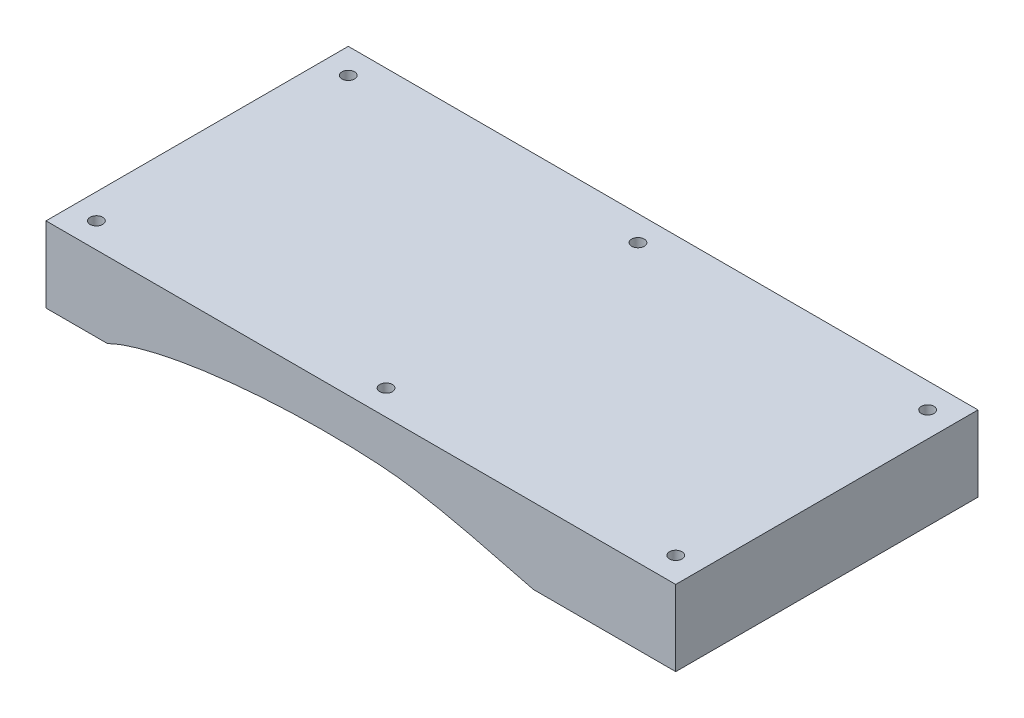
SolidWorks part; units mm, degrees
material "PTFE (general)"
ref_plane "Front Plane" through (0, 0, 0) normal (0, 0, 1) x (1, 0, 0)
ref_plane "Top Plane" through (0, 0, 0) normal (0, 1, 0) x (1, 0, 0)
ref_plane "Right Plane" through (0, 0, 0) normal (1, 0, 0) x (0, 0, -1)
curve "Curve1"
  spline degree 3 poles (0.9879, -0.001, 0) (1.003, 0, 0) (0.9879, 0.001, 0) (0.9756, 0.0029, 0) (0.9509, 0.006, 0) (0.9257, 0.0111, 0) (0.8922, 0.0189, 0) (0.85, 0.0292, 0) (0.8, 0.0421, 0) (0.7501, 0.0546, 0) (0.7002, 0.0662, 0) (0.6502, 0.0761, 0) (0.6002, 0.0839, 0) (0.5501, 0.0876, 0) (0.5, 0.0897, 0) (0.45, 0.0902, 0) (0.4, 0.0894, 0) (0.35, 0.0872, 0) (0.2999, 0.0837, 0) (0.2499, 0.0787, 0) (0.1999, 0.0722, 0) (0.1498, 0.0637, 0) (0.1081, 0.0545, 0) (0.0748, 0.0453, 0) (0.0496, 0.0371, 0) (0.0287, 0.0286, 0) (0.0146, 0.0212, 0) (0.0081, 0.0164, 0) (0.0041, 0.0124, 0) (0.0008, 0.0072, 0) (-0.0004, 0, 0) (0.0008, -0.0072, 0) (0.0041, -0.0124, 0) (0.0081, -0.0164, 0) (0.0146, -0.0212, 0) (0.0287, -0.0286, 0) (0.0496, -0.0371, 0) (0.0748, -0.0453, 0) (0.1081, -0.0545, 0) (0.1498, -0.0637, 0) (0.1999, -0.0722, 0) (0.2499, -0.0787, 0) (0.2999, -0.0837, 0) (0.35, -0.0872, 0) (0.4, -0.0894, 0) (0.45, -0.0902, 0) (0.5, -0.0897, 0) (0.5501, -0.0876, 0) (0.6002, -0.0839, 0) (0.6502, -0.0761, 0) (0.7002, -0.0662, 0) (0.7501, -0.0546, 0) (0.8, -0.0421, 0) (0.842, -0.0313, 0) (0.8753, -0.0231, 0) (0.9087, -0.015, 0) (0.9412, -0.0072, 0) (0.9756, -0.0029, 0) (0.9879, -0.001, 0) (1.003, 0, 0) (0.9879, 0.001, 0) knots -0.02448 -0.010984 -0.00276 0 0.00276 0.010984 0.02448 0.035911 0.049305 0.074294 0.099343 0.12436 0.149265 0.17401 0.198547 0.222904 0.247201 0.271478 0.295756 0.320055 0.344391 0.368787 0.393273 0.417901 0.442781 0.455382 0.46816 0.481314 0.488256 0.491308 0.493017 0.496509 0.500002 0.503494 0.506986 0.508696 0.511748 0.518689 0.531843 0.544621 0.557222 0.582102 0.60673 0.631216 0.655612 0.679949 0.704247 0.728526 0.752803 0.777099 0.801456 0.825994 0.850739 0.875644 0.90066 0.925709 0.938747 0.950698 0.97552 0.989016 0.99724 1 1.00276 1.010984 1.02448 periodic
sketch "Sketch1" plane through (0, 0, 0) normal (0, 0, 1) x (1, 0, 0)
  line L0 (0, 0) -> (-40, 0)
  line L1 (175, 0.3825) -> (175, -0.391) construction
  line L2 (-40, 0) -> (-40, 50)
  line L3 (-40, 50) -> (250, 50)
  line L4 (250, 50) -> (250, 0)
  line L5 (-40, 0) -> (-40, 5)
  line L6 (250, 0) -> (250, 5)
  line L7 (-40, 5) -> (4.407, 5)
  line L8 (250, 5) -> (173.4906, 5)
  line L10 (-20, 5) -> (-20, 35)
  line L11 (-20, 35) -> (230, 35)
  line L12 (230, 35) -> (230, 5)
  line L13 (0, 0) -> (160, 0) construction
  arc A0 (175, 0.3825) -> (175, -0.391) centre (174.9067, -0.0042) cw
  spline S0 degree 3 poles (197.5872, -0.2056) (200.6063, 0) (197.5868, 0.2056) (195.1252, 0.5776) (190.1802, 1.1937) (185.1344, 2.2203) (178.4338, 3.785) (169.9915, 5.8479) (160.0056, 8.4214) (150.023, 10.9293) (140.0327, 13.2422) (130.0396, 15.2245) (120.0397, 16.7768) (110.0103, 17.5195) (100.0043, 17.9361) (89.9996, 18.0394) (79.996, 17.8821) (69.9921, 17.4474) (59.988, 16.7376) (49.9816, 15.7477) (39.9717, 14.4342) (29.9504, 12.7437) (21.617, 10.9015) (14.9666, 9.0538) (9.9288, 7.4256) (5.7467, 5.7158) (2.9192, 4.2411) (1.6254, 3.2787) (0.81, 2.4889) (0.1663, 1.4484) (-0.0831, 0) (0.1663, -1.4484) (0.81, -2.4889) (1.6254, -3.2787) (2.9192, -4.2411) (5.7467, -5.7158) (9.9288, -7.4256) (14.9666, -9.0538) (21.617, -10.9015) (29.9504, -12.7437) (39.9717, -14.4342) (49.9816, -15.7477) (59.988, -16.7376) (69.9921, -17.4474) (79.996, -17.8821) (89.9996, -18.0394) (100.0043, -17.9361) (110.0103, -17.5195) (120.0397, -16.7768) (130.0396, -15.2245) (140.0327, -13.2422) (150.0229, -10.9292) (160.0058, -8.4217) (168.4006, -6.2567) (175.0619, -4.611) (181.7476, -3.0075) (188.2352, -1.4431) (195.1191, -0.5775) (197.5872, -0.2056) (200.6063, 0) (197.5868, 0.2056) knots -0.02448 -0.010984 -0.00276 0 0.00276 0.010984 0.02448 0.035911 0.049305 0.074294 0.099343 0.12436 0.149265 0.17401 0.198547 0.222904 0.247201 0.271478 0.295756 0.320055 0.344391 0.368787 0.393273 0.417901 0.442781 0.455382 0.46816 0.481314 0.488256 0.491308 0.493017 0.496509 0.500002 0.503494 0.506986 0.508696 0.511748 0.518689 0.531843 0.544621 0.557222 0.582102 0.60673 0.631216 0.655612 0.679949 0.704247 0.728526 0.752803 0.777099 0.801456 0.825994 0.850739 0.875644 0.90066 0.925709 0.938747 0.950698 0.97552 0.989016 0.99724 1 1.00276 1.010984 1.02448 only from (200, 0) to (200, 0)
  spline S1 degree 3 poles (175, -0.391) (172.0852, -1.0939) (166.2646, -2.4977) (154.6086, -5.1021) (140.0385, -8.0995) (122.5354, -11.2892) (105.0361, -14.0584) (87.5366, -16.3245) (70.0311, -17.928) (55.4199, -18.5013) (43.7404, -18.2704) (34.9711, -17.6651) (26.1801, -16.4934) (18.8666, -14.858) (13.0417, -12.9137) (8.568, -10.9367) (4.8344, -8.5647) (1.3476, -5.1963) (-0.8977, -0.0042) (1.3476, 5.1878) (4.8344, 8.5562) (8.568, 10.9282) (13.0417, 12.9052) (18.8666, 14.8495) (26.1801, 16.4849) (34.9711, 17.6567) (43.7404, 18.2619) (55.4199, 18.4929) (70.0311, 17.9195) (87.5366, 16.316) (105.0361, 14.0499) (122.5354, 11.2807) (140.0385, 8.0911) (154.6086, 5.0937) (166.2646, 2.4892) (172.0852, 1.0855) (175, 0.3825) knots 0 0 0 0 0.024528 0.048982 0.097703 0.146209 0.194518 0.242628 0.290539 0.338289 0.362155 0.386077 0.410161 0.434654 0.447248 0.460338 0.47462 0.483093 0.5 0.516907 0.52538 0.539662 0.552752 0.565346 0.589839 0.613923 0.637845 0.661711 0.709461 0.757372 0.805482 0.853791 0.902297 0.951018 0.975472 1 1 1 1 construction
  point P15 (174.9067, 0)
  point P17 (186.0106, 9.1612)
  point P21 (4.407, 5)
  point P22 (195.2937, 6.8)
  point P23 (0, 0)
  point P24 (172.3706, 5.2767)
  point P25 (0, 0)
  dimension "D6" = 15
  dimension "D1" = 50
  dimension "D2" = 40
  dimension "D3" = 175
  dimension "D4" = 5
  dimension "D5" = 5
  dimension "D7" = 20
  dimension "D8" = 20
  dimension "D9" = 90
  dimension "D10" = 50
  dimension "D11" = 250
extrude "Boss-Extrude1" add sketch "Sketch1" along normal blind 120 contours L7 S1 L8 L12 L11 L10
sketch "Sketch2" plane through (0, 35, 0) normal (0, 1, 0) x (1, 0, 0)
  line L0 (-20, -60) -> (60, -60)
  line L1 (-20, -120) -> (-20, 0) construction
  circle A0 centre (60, -60) radius 10
ref_plane "Plane1" through (0, 25, 0) normal (0, 1, 0) x (1, 0, 0)
sketch "Sketch5" plane through (0, 25, 0) normal (0, 1, 0) x (1, 0, 0)
  line L0 (-20, -120) -> (-20, 0) construction
  line L1 (-10, 0) -> (-20, 0) construction
  line L2 (-10, 0) -> (-10, -10) construction
  line L3 (-10, -10) -> (-20, -10) construction
  line L4 (-20, 0) -> (-20, -10) construction
  line L5 (-10, -10) -> (220, -10) construction
  line L6 (230, 0) -> (220, 0) construction
  line L7 (230, 0) -> (230, -10) construction
  line L8 (230, -10) -> (220, -10) construction
  line L9 (220, 0) -> (220, -10) construction
  line L10 (230, -120) -> (220, -120) construction
  line L11 (230, -120) -> (230, -110) construction
  line L12 (230, -110) -> (220, -110) construction
  line L13 (220, -120) -> (220, -110) construction
  line L14 (-20, -120) -> (-10, -120) construction
  line L15 (-20, -120) -> (-20, -110) construction
  line L16 (-20, -110) -> (-10, -110) construction
  line L17 (-10, -120) -> (-10, -110) construction
  line L18 (-10, -10) -> (-10, -110) construction
  line L19 (-10, -110) -> (220, -110) construction
  line L20 (220, -110) -> (220, -10) construction
  point P4 (220, -5)
  dimension "D1" = 10
  dimension "D2" = 10
  dimension "D3" = 10
hole_wizard "Ø5.0mm Dowel Hole1" positions "Sketch9" profile "Sketch10" hole size "Ø5.0" standard "ISO"
sketch "Sketch9" plane through (0, 25, 0) normal (0, 1, 0) x (1, 0, 0)
  line L0 (-10, -110) -> (220, -110) construction
  line L1 (-10, -10) -> (220, -10) construction
  point P0 (-10, -10)
  point P3 (220, -10)
  point P6 (220, -110)
  point P9 (105, -110)
  point P13 (-10, -110)
  point P16 (105, -10)
sketch "Sketch10" plane through (-10, 25, 10) normal (1, 0, 0) x (0, 0, -1)
  line L0 (0, 0) -> (0, 10)
  line L1 (0, 10) -> (2.5, 10)
  line L2 (2.5, 10) -> (2.5, 0)
  line L5 (2.5, 0) -> (0, 0)
  line L11 (0, -6.35) -> (0, 107.95) construction
  dimension "Thru Hole Dia." = 5
  dimension "Thru Hole Depth" = 10
hole_wizard "Ø10.0mm Dowel Hole1" positions "Sketch12" profile "Sketch13" hole size "Ø10.0" standard "ISO"
sketch "Sketch12" plane through (0, 25, 0) normal (0, 1, 0) x (1, 0, 0)
  line L0 (-10, -10) -> (220, -10) construction
  line L1 (-10, -110) -> (220, -110) construction
  point P0 (-10, -10)
  point P3 (105, -10)
  point P7 (220, -10)
  point P10 (220, -110)
  point P13 (105, -110)
  point P17 (-10, -110)
sketch "Sketch13" plane through (-10, 25, 10) normal (1, 0, 0) x (0, 0, 1)
  line L0 (0, 0) -> (0, 20)
  line L1 (0, 20) -> (5, 20)
  line L2 (5, 20) -> (5, 0)
  line L5 (5, 0) -> (0, 0)
  line L11 (0, -6.35) -> (0, 107.95) construction
  dimension "Thru Hole Dia." = 10
  dimension "Thru Hole Depth" = 20
